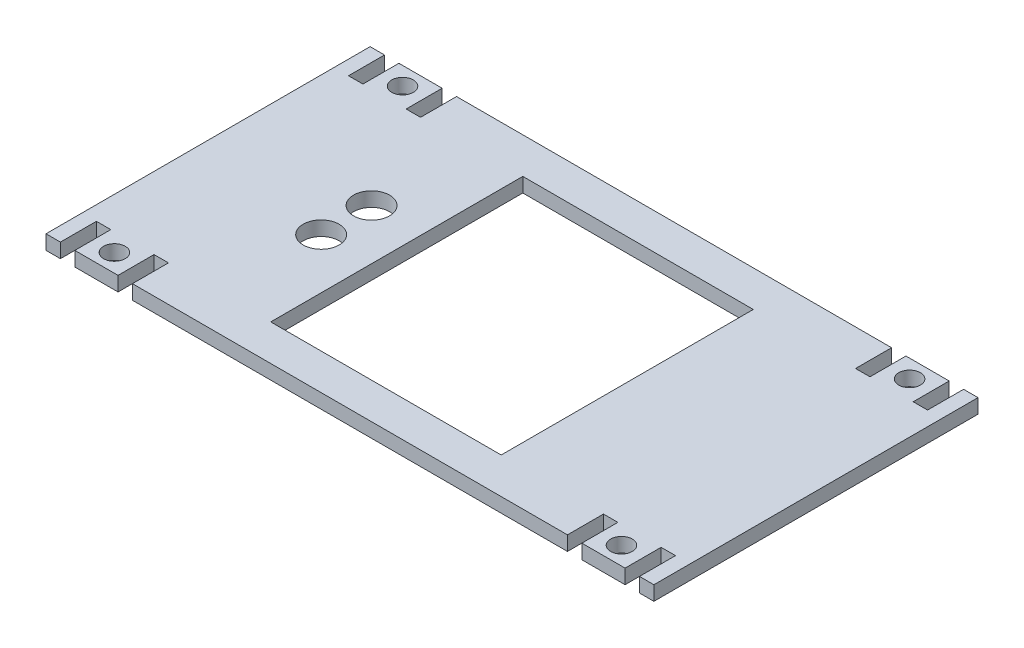
SolidWorks part; units mm, degrees
ref_plane "Front Plane" through (0, 0, 0) normal (0, 0, 1) x (1, 0, 0)
ref_plane "Top Plane" through (0, 0, 0) normal (0, 1, 0) x (1, 0, 0)
ref_plane "Right Plane" through (0, 0, 0) normal (1, 0, 0) x (0, 0, -1)
sketch "Sketch1" plane through (0, 0, 0) normal (0, 1, 0) x (1, 0, 0)
  line L0 (42.2, 45) -> (42.2, 0) construction
  line L1 (0, 0) -> (2, 0)
  line L2 (0, 0) -> (0, 45)
  line L3 (0, 45) -> (2, 45)
  line L4 (84.4, 0) -> (84.4, 45)
  line L5 (0, 22.5) -> (84.4, 22.5) construction
  line L6 (7, 45) -> (7, 42.5) construction
  line L7 (7, 42.5) -> (11, 42.5) construction
  line L9 (10, 40) -> (12, 40)
  line L10 (10, 40) -> (10, 45)
  line L12 (12, 40) -> (12, 45)
  line L13 (10, 40) -> (12, 45) construction
  line L14 (10, 45) -> (12, 40) construction
  line L15 (2, 40) -> (2, 45)
  line L16 (4, 40) -> (2, 40)
  line L17 (4, 40) -> (4, 45)
  line L19 (72.4, 40) -> (72.4, 45)
  line L20 (74.4, 40) -> (72.4, 40)
  line L21 (74.4, 40) -> (74.4, 45)
  line L22 (80.4, 40) -> (80.4, 45)
  line L23 (80.4, 40) -> (82.4, 40)
  line L24 (82.4, 40) -> (82.4, 45)
  line L27 (12, 5) -> (12, 0)
  line L28 (10, 5) -> (12, 5)
  line L29 (10, 5) -> (10, 0)
  line L30 (4, 5) -> (4, 0)
  line L31 (4, 5) -> (2, 5)
  line L32 (2, 5) -> (2, 0)
  line L35 (82.4, 5) -> (82.4, 0)
  line L36 (80.4, 5) -> (82.4, 5)
  line L37 (80.4, 5) -> (80.4, 0)
  line L38 (74.4, 5) -> (74.4, 0)
  line L39 (74.4, 5) -> (72.4, 5)
  line L40 (72.4, 5) -> (72.4, 0)
  line L42 (4, 0) -> (10, 0)
  line L43 (12, 0) -> (72.4, 0)
  line L44 (4, 45) -> (10, 45)
  line L45 (12, 45) -> (72.4, 45)
  line L46 (82.4, 45) -> (84.4, 45)
  line L47 (74.4, 45) -> (80.4, 45)
  line L48 (82.4, 0) -> (84.4, 0)
  line L49 (74.4, 0) -> (80.4, 0)
  circle A0 centre (7, 42.5) radius 1.5
  circle A1 centre (77.4, 42.5) radius 1.5
  circle A2 centre (7, 2.5) radius 1.5
  circle A3 centre (77.4, 2.5) radius 1.5
  dimension "D3" = 3
  dimension "D1" = 84.4
  dimension "D2" = 45
  dimension "D4" = 2
  dimension "D5" = 5
  dimension "D7" = 2
  dimension "D8" = 6
extrude "Boss-Extrude1" add sketch "Sketch1" along normal blind 2
sketch "Sketch2" plane through (0, 2, 0) normal (0, 1, 0) x (1, 0, 0)
  line L0 (42.2, 45) -> (42.2, 0) construction
  line L1 (72.4, 45) -> (12, 45) construction
  line L2 (12, 0) -> (72.4, 0) construction
  line L3 (0, 22.5) -> (42.2, 22.5) construction
  line L4 (0, 45) -> (0, 0) construction
  line L6 (58.2, 5) -> (26.2, 5)
  line L7 (58.2, 5) -> (58.2, 40)
  line L8 (58.2, 40) -> (26.2, 40)
  line L9 (26.2, 5) -> (26.2, 40)
  line L10 (58.2, 5) -> (26.2, 40) construction
  line L11 (58.2, 40) -> (26.2, 5) construction
  dimension "D1" = 32
  dimension "D2" = 35
extrude "Cut-Extrude1" cut sketch "Sketch2" against normal blind 10
sketch "Sketch3" plane through (0, 2, 0) normal (0, 1, 0) x (1, 0, 0)
  line L0 (0, 22.5) -> (26.2, 22.5) construction
  line L1 (0, 45) -> (0, 0) construction
  line L2 (26.2, 40) -> (26.2, 5) construction
  line L3 (19.2, 22.5) -> (19.2, 26) construction
  circle A0 centre (19.2, 26) radius 2.5
  circle A1 centre (19.2, 19) radius 2.5
  dimension "D1" = 5
  dimension "D2" = 7
  dimension "D3" = 7
extrude "Cut-Extrude2" cut sketch "Sketch3" against normal blind 10
